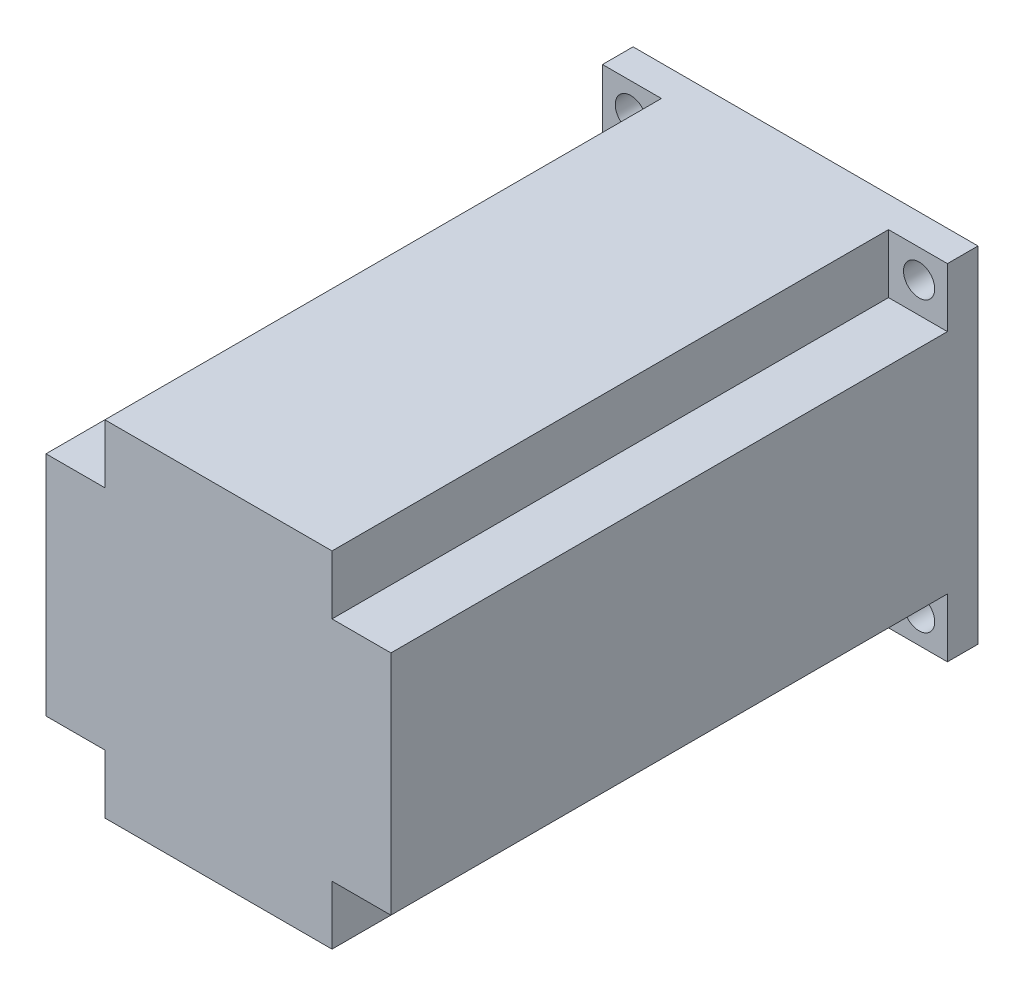
SolidWorks part; units mm, degrees
ref_plane "前视基准面" through (0, 0, 0) normal (0, 0, 1) x (1, 0, 0)
ref_plane "上视基准面" through (0, 0, 0) normal (0, 1, 0) x (1, 0, 0)
ref_plane "右视基准面" through (0, 0, 0) normal (1, 0, 0) x (0, 0, -1)
sketch "草图1" plane through (0, 0, 0) normal (0, 0, 1) x (1, 0, 0)
  line L1 (-23.57, 23.57) -> (23.57, 23.57) construction
  line L2 (-23.57, 23.57) -> (-23.57, -23.57) construction
  line L3 (-23.57, -23.57) -> (23.57, -23.57) construction
  line L4 (23.57, 23.57) -> (23.57, -23.57) construction
  line L5 (-23.57, 23.57) -> (23.57, -23.57) construction
  line L6 (-23.57, -23.57) -> (23.57, 23.57) construction
  line L7 (-28.2, 28.2) -> (28.2, 28.2)
  line L8 (-28.2, 28.2) -> (-28.2, -28.2)
  line L9 (-28.2, -28.2) -> (28.2, -28.2)
  line L10 (28.2, 28.2) -> (28.2, -28.2)
  line L11 (-28.2, 28.2) -> (28.2, -28.2) construction
  line L12 (-28.2, -28.2) -> (28.2, 28.2) construction
  circle A0 centre (23.57, 23.57) radius 2.55
  circle A1 centre (23.57, -23.57) radius 2.55
  circle A2 centre (-23.57, -23.57) radius 2.55
  circle A3 centre (-23.57, 23.57) radius 2.55
  point P0 (0, 0)
  point P7 (0, 0)
  dimension "D2" = 5.1
  dimension "D1" = 47.14
  dimension "D4" = 56.4
  dimension "D3" = 4
extrude "凸台-拉伸1" add sketch "草图1" along normal blind 96
sketch "草图2" plane through (0, 0, 96) normal (0, 0, 1) x (1, 0, 0)
  line L0 (-23.57, -23.57) -> (23.57, 23.57) construction
  line L5 (-28.57, 28.57) -> (-18.57, 28.57)
  line L6 (-28.57, 28.57) -> (-28.57, 18.57)
  line L7 (-28.57, 18.57) -> (-18.57, 18.57)
  line L8 (-18.57, 28.57) -> (-18.57, 18.57)
  line L9 (-28.57, 28.57) -> (-18.57, 18.57) construction
  line L10 (-28.57, 18.57) -> (-18.57, 28.57) construction
  line L11 (28.57, 28.57) -> (28.57, 18.57)
  line L12 (28.57, 28.57) -> (18.57, 28.57)
  line L13 (18.57, 28.57) -> (18.57, 18.57)
  line L14 (28.57, 18.57) -> (18.57, 18.57)
  line L15 (28.57, 28.57) -> (18.57, 18.57) construction
  line L16 (18.57, 28.57) -> (28.57, 18.57) construction
  line L17 (28.57, -28.57) -> (18.57, -28.57)
  line L18 (28.57, -28.57) -> (28.57, -18.57)
  line L19 (28.57, -18.57) -> (18.57, -18.57)
  line L20 (18.57, -28.57) -> (18.57, -18.57)
  line L21 (28.57, -28.57) -> (18.57, -18.57) construction
  line L22 (28.57, -18.57) -> (18.57, -28.57) construction
  line L23 (-28.57, -28.57) -> (-28.57, -18.57)
  line L24 (-28.57, -28.57) -> (-18.57, -28.57)
  line L25 (-18.57, -28.57) -> (-18.57, -18.57)
  line L26 (-28.57, -18.57) -> (-18.57, -18.57)
  line L27 (-28.57, -28.57) -> (-18.57, -18.57) construction
  line L28 (-18.57, -28.57) -> (-28.57, -18.57) construction
  point P0 (-23.57, 23.57)
  point P12 (23.57, 23.57)
  point P17 (23.57, -23.57)
  point P22 (-23.57, -23.57)
  circle M5 centre (-23.57, -23.57) radius 2.55
  circle M6 centre (23.57, 23.57) radius 2.55
  line M7 (28.2, -28.2) -> (28.2, 28.2)
  line M8 (28.2, 28.2) -> (-28.2, 28.2)
  line M9 (-28.2, 28.2) -> (-28.2, -28.2)
  line M10 (-28.2, -28.2) -> (28.2, -28.2)
  circle M11 centre (23.57, -23.57) radius 2.55
  dimension "D1" = 10
  dimension "D2" = 4
extrude "切除-拉伸1" cut sketch "草图2" against normal blind 91 contours L26 L25 M9 M10 M5 | L20 L19 M10 M7 M11 | L14 L13 M7 M8 M6 | L5 L8 L7 L6
sketch "草图3" plane through (0, 0, 0) normal (0, 0, -1) x (-1, 0, 0)
  circle A0 centre (0, 0) radius 4
  dimension "D1" = 8
extrude "凸台-拉伸2" add sketch "草图3" along normal blind 21
sketch "草图4" plane through (0, 0, 0) normal (0, 0, -1) x (-1, 0, 0)
  circle A0 centre (0, 0) radius 19.05
  dimension "D1" = 38.1
extrude "凸台-拉伸3" add sketch "草图4" along normal blind 1.6
